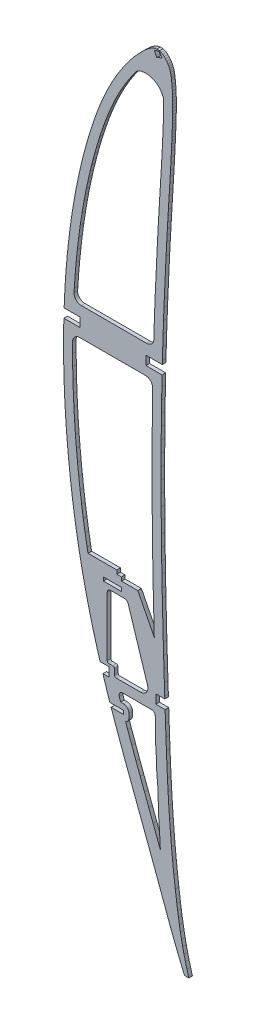
SolidWorks part; units mm, degrees
ref_plane "前视基准面" through (0, 0, 0) normal (0, 0, 1) x (1, 0, 0)
ref_plane "上视基准面" through (0, 0, 0) normal (0, 1, 0) x (1, 0, 0)
ref_plane "右视基准面" through (0, 0, 0) normal (1, 0, 0) x (0, 0, -1)
sketch "Model" plane through (0, 0, 0) normal (0, 0, 1) x (1, 0, 0)
  line L0 (54.2913, 117.0842) -> (54.2913, 119.0842)
  line L1 (43.2867, 175.5953) -> (43.2867, 177.5953)
  line L2 (47.5499, 117.0842) -> (54.2913, 117.0842)
  line L3 (54.2913, 119.0842) -> (46.8729, 119.0842)
  line L4 (41.4413, 135.9645) -> (46.4413, 135.9645)
  line L5 (46.4413, 135.9645) -> (46.4413, 130.9645)
  line L6 (72.3504, 135.9645) -> (72.3504, 130.9645)
  line L7 (72.3504, 135.9645) -> (77.3504, 135.9645)
  line L8 (77.5205, 130.9645) -> (72.3504, 130.9645)
  line L9 (42.9847, 130.9645) -> (46.4413, 130.9645)
  line L10 (45.5666, 122.9434) -> (43.4876, 129.3408)
  line L11 (43.4876, 129.3408) -> (42.9847, 130.9645)
  line L12 (41.4413, 135.9645) -> (40.6109, 138.7843)
  line L13 (77.1998, 140.4674) -> (77.3066, 137.2545)
  line L14 (77.3066, 137.2545) -> (77.3504, 135.9645)
  line L15 (77.5205, 130.9645) -> (77.5251, 130.8269)
  line L16 (77.5251, 130.8269) -> (77.7487, 124.3996)
  line L17 (77.7487, 124.3996) -> (77.9822, 117.9746)
  line L18 (77.9822, 117.9746) -> (78.009, 117.2896)
  line L19 (88.29, 8.5437) -> (88.0966, 8.9921)
  line L20 (88.0966, 8.9921) -> (86.7544, 12.1535)
  line L21 (86.7544, 12.1535) -> (85.4358, 15.3251)
  line L22 (85.4358, 15.3251) -> (84.1437, 18.5087)
  line L23 (84.1437, 18.5087) -> (82.9023, 21.6546)
  line L24 (82.9023, 21.6546) -> (81.6876, 24.8086)
  line L25 (81.6876, 24.8086) -> (80.4935, 27.9715)
  line L26 (80.4935, 27.9715) -> (79.3151, 31.1411)
  line L27 (79.3151, 31.1411) -> (78.1486, 34.3143)
  line L28 (78.1486, 34.3143) -> (76.9859, 37.4896)
  line L29 (76.9859, 37.4896) -> (75.8232, 40.6669)
  line L30 (75.8232, 40.6669) -> (73.4872, 47.013)
  line L31 (73.4872, 47.013) -> (71.1336, 53.3494)
  line L32 (71.1336, 53.3494) -> (68.7682, 59.6802)
  line L33 (68.7682, 59.6802) -> (66.394, 66.0067)
  line L34 (66.394, 66.0067) -> (64.0128, 72.3319)
  line L35 (64.0128, 72.3319) -> (61.6296, 78.6569)
  line L36 (61.6296, 78.6569) -> (59.2463, 84.986)
  line L37 (59.2463, 84.986) -> (56.8823, 91.2849)
  line L38 (56.8823, 91.2849) -> (54.5361, 97.5885)
  line L39 (54.5361, 97.5885) -> (52.2195, 103.9015)
  line L40 (52.2195, 103.9015) -> (49.9444, 110.2283)
  line L41 (49.9444, 110.2283) -> (47.9557, 115.9083)
  line L42 (78.009, 117.2896) -> (78.2336, 111.5505)
  line L43 (78.2336, 111.5505) -> (78.51, 105.1294)
  line L44 (78.51, 105.1294) -> (78.8173, 98.7097)
  line L45 (78.8173, 98.7097) -> (79.1646, 92.2908)
  line L46 (79.1646, 92.2908) -> (79.5579, 85.8728)
  line L47 (79.5579, 85.8728) -> (80.0046, 79.4492)
  line L48 (80.0046, 79.4492) -> (80.509, 73.0311)
  line L49 (80.509, 73.0311) -> (81.0722, 66.6185)
  line L50 (81.0722, 66.6185) -> (81.7013, 60.2119)
  line L51 (81.7013, 60.2119) -> (82.3972, 53.8101)
  line L52 (82.3972, 53.8101) -> (83.1659, 47.4146)
  line L53 (83.1659, 47.4146) -> (84.0104, 41.0243)
  line L54 (84.0104, 41.0243) -> (84.4661, 37.8092)
  line L55 (84.4661, 37.8092) -> (84.9486, 34.5991)
  line L56 (84.9486, 34.5991) -> (85.4639, 31.3946)
  line L57 (85.4639, 31.3946) -> (86.0178, 28.1987)
  line L58 (86.0178, 28.1987) -> (86.6183, 25.0129)
  line L59 (86.6183, 25.0129) -> (87.2714, 21.8383)
  line L60 (87.2714, 21.8383) -> (87.983, 18.6764)
  line L61 (87.983, 18.6764) -> (88.7727, 15.4677)
  line L62 (88.7727, 15.4677) -> (89.6209, 12.2737)
  line L63 (89.6209, 12.2737) -> (90.5165, 9.0917)
  line L64 (90.5165, 9.0917) -> (90.6781, 8.5437)
  line L65 (90.6781, 8.5437) -> (88.29, 8.5437)
  line L66 (72.0426, 125.2144) -> (72.2183, 117.7571)
  line L67 (72.2183, 117.7571) -> (72.3082, 111.0082)
  line L68 (72.3082, 111.0082) -> (72.7111, 105.0949)
  line L69 (72.7111, 105.0949) -> (72.8903, 98.4132)
  line L70 (72.8903, 98.4132) -> (73.4718, 91.9672)
  line L71 (73.4718, 91.9672) -> (73.6969, 85.8323)
  line L72 (73.6969, 85.8323) -> (73.7913, 79.2782)
  line L73 (73.7913, 79.2782) -> (74.3141, 72.7011)
  line L74 (74.3141, 72.7011) -> (74.6648, 66.3846)
  line L75 (74.6648, 66.3846) -> (74.8646, 62.2836)
  line L76 (74.8646, 62.2836) -> (73.2043, 66.7077)
  line L77 (73.2043, 66.7077) -> (70.8228, 73.0338)
  line L78 (70.8228, 73.0338) -> (68.4394, 79.3594)
  line L79 (68.4394, 79.3594) -> (66.0566, 85.6871)
  line L80 (66.0566, 85.6871) -> (63.694, 91.9824)
  line L81 (63.694, 91.9824) -> (61.3503, 98.2791)
  line L82 (61.3503, 98.2791) -> (59.0376, 104.5817)
  line L83 (59.0376, 104.5817) -> (56.7675, 110.8944)
  line L84 (56.7675, 110.8944) -> (55.6091, 114.203)
  line L85 (57.4411, 116.9663) -> (57.4411, 119.1909)
  line L86 (54.4411, 122.1909) -> (52.8701, 122.1909)
  line L87 (52.8701, 122.1909) -> (52.0797, 124.526)
  line L88 (53.9741, 127.1673) -> (70.0431, 127.1673)
  line L89 (45.3607, 138.4853) -> (45.3607, 171.1109)
  line L90 (47.3607, 173.1109) -> (55.0651, 173.1109)
  line L91 (56.9714, 171.716) -> (67.7492, 137.7647)
  line L92 (50.459, 132.5544) -> (63.9367, 132.5544)
  line L93 (47.5499, 117.0842) -> (47.9557, 115.9083)
  line L94 (43.2867, 175.5953) -> (53.2867, 175.5953)
  line L95 (46.8729, 119.0842) -> (45.5666, 122.9434)
  line L96 (53.2867, 175.5953) -> (53.2867, 177.5953)
  line L97 (50.7445, 177.5953) -> (53.2867, 177.5953)
  line L98 (50.7445, 182.5953) -> (53.2867, 182.5953)
  line L99 (21.4859, 295.9645) -> (21.7513, 302.1442)
  line L100 (21.7513, 302.1442) -> (22.12, 308.5794)
  line L101 (22.12, 308.5794) -> (22.5856, 315.0859)
  line L102 (22.5856, 315.0859) -> (23.1507, 321.5827)
  line L103 (23.1507, 321.5827) -> (23.8184, 328.069)
  line L104 (23.8184, 328.069) -> (24.5928, 334.5419)
  line L105 (24.5928, 334.5419) -> (25.481, 340.9998)
  line L106 (25.481, 340.9998) -> (26.486, 347.4408)
  line L107 (26.486, 347.4408) -> (27.612, 353.862)
  line L108 (27.612, 353.862) -> (28.2359, 357.1334)
  line L109 (28.2359, 357.1334) -> (28.8931, 360.3981)
  line L110 (28.8931, 360.3981) -> (29.5827, 363.6553)
  line L111 (29.5827, 363.6553) -> (30.3077, 366.904)
  line L112 (30.3077, 366.904) -> (31.066, 370.1462)
  line L113 (31.066, 370.1462) -> (31.8597, 373.3799)
  line L114 (31.8597, 373.3799) -> (32.6898, 376.6052)
  line L115 (32.6898, 376.6052) -> (33.5785, 379.9081)
  line L116 (33.5785, 379.9081) -> (34.5079, 383.1987)
  line L117 (34.5079, 383.1987) -> (35.4798, 386.4773)
  line L118 (35.4798, 386.4773) -> (36.4974, 389.7408)
  line L119 (36.4974, 389.7408) -> (37.5627, 392.9903)
  line L120 (37.5627, 392.9903) -> (38.6787, 396.2231)
  line L121 (38.6787, 396.2231) -> (39.8486, 399.4392)
  line L122 (39.8486, 399.4392) -> (40.4777, 401.1002)
  line L123 (40.4777, 401.1002) -> (41.1222, 402.7549)
  line L124 (72.0622, 328.3115) -> (71.885, 324.0494)
  line L125 (71.885, 324.0494) -> (71.6364, 317.5859)
  line L126 (71.6364, 317.5859) -> (71.408, 311.1173)
  line L127 (71.408, 311.1173) -> (71.2921, 305.8066)
  line L128 (67.2931, 301.8939) -> (30.9809, 301.8939)
  line L129 (26.9874, 306.1227) -> (27.1097, 308.2579)
  line L130 (27.1097, 308.2579) -> (27.5701, 314.6907)
  line L131 (27.5701, 314.6907) -> (28.1285, 321.11)
  line L132 (28.1285, 321.11) -> (28.7879, 327.516)
  line L133 (28.7879, 327.516) -> (29.5522, 333.9043)
  line L134 (29.5522, 333.9043) -> (30.4282, 340.2737)
  line L135 (30.4282, 340.2737) -> (31.419, 346.6235)
  line L136 (31.419, 346.6235) -> (32.5304, 352.9618)
  line L137 (32.5304, 352.9618) -> (33.1426, 356.1716)
  line L138 (33.1426, 356.1716) -> (33.7898, 359.3869)
  line L139 (33.7898, 359.3869) -> (34.4686, 362.593)
  line L140 (34.4686, 362.593) -> (35.1821, 365.7901)
  line L141 (35.1821, 365.7901) -> (35.9283, 368.9809)
  line L142 (35.9283, 368.9809) -> (36.7088, 372.1608)
  line L143 (36.7088, 372.1608) -> (37.5251, 375.3324)
  line L144 (37.5251, 375.3324) -> (38.3987, 378.5789)
  line L145 (38.3987, 378.5789) -> (39.3109, 381.8087)
  line L146 (39.3109, 381.8087) -> (40.2636, 385.0224)
  line L147 (40.2636, 385.0224) -> (41.2599, 388.2177)
  line L148 (41.2599, 388.2177) -> (42.3017, 391.3956)
  line L149 (42.3017, 391.3956) -> (43.3916, 394.5525)
  line L150 (43.3916, 394.5525) -> (44.5361, 397.699)
  line L151 (44.5361, 397.699) -> (45.1453, 399.3073)
  line L152 (45.1453, 399.3073) -> (45.7724, 400.9174)
  line L153 (40.6109, 138.7843) -> (39.6813, 141.9408)
  line L154 (39.6813, 141.9408) -> (37.9112, 148.2786)
  line L155 (37.9112, 148.2786) -> (36.2331, 154.6415)
  line L156 (36.2331, 154.6415) -> (34.647, 161.0284)
  line L157 (34.647, 161.0284) -> (33.1549, 167.4384)
  line L158 (33.1549, 167.4384) -> (31.758, 173.8716)
  line L159 (31.758, 173.8716) -> (30.4769, 180.2187)
  line L160 (30.4769, 180.2187) -> (29.2883, 186.5809)
  line L161 (29.2883, 186.5809) -> (28.189, 192.9591)
  line L162 (28.189, 192.9591) -> (27.1742, 199.3509)
  line L163 (27.1742, 199.3509) -> (26.244, 205.7564)
  line L164 (26.244, 205.7564) -> (25.3942, 212.1734)
  line L165 (25.3942, 212.1734) -> (24.6221, 218.6029)
  line L166 (24.6221, 218.6029) -> (23.9293, 225.0007)
  line L167 (23.9293, 225.0007) -> (23.3124, 231.4049)
  line L168 (23.3124, 231.4049) -> (22.7713, 237.8144)
  line L169 (22.7713, 237.8144) -> (22.3071, 244.2283)
  line L170 (22.3071, 244.2283) -> (21.9207, 250.6485)
  line L171 (21.9207, 250.6485) -> (21.6121, 257.0742)
  line L172 (21.6121, 257.0742) -> (21.3834, 263.5043)
  line L173 (21.3834, 263.5043) -> (21.2343, 269.946)
  line L174 (21.2343, 269.946) -> (21.1672, 276.3872)
  line L175 (21.1672, 276.3872) -> (21.1843, 282.828)
  line L176 (21.1843, 282.828) -> (21.2855, 289.2686)
  line L177 (21.2855, 289.2686) -> (21.3104, 290.9645)
  line L178 (34.7295, 184.6822) -> (34.2097, 187.4647)
  line L179 (34.2097, 187.4647) -> (33.122, 193.7757)
  line L180 (33.122, 193.7757) -> (32.1176, 200.1022)
  line L181 (32.1176, 200.1022) -> (31.1966, 206.4439)
  line L182 (31.1966, 206.4439) -> (30.3549, 212.7997)
  line L183 (30.3549, 212.7997) -> (29.5899, 219.1701)
  line L184 (29.5899, 219.1701) -> (28.9034, 225.5096)
  line L185 (28.9034, 225.5096) -> (28.2922, 231.855)
  line L186 (28.2922, 231.855) -> (27.7561, 238.2052)
  line L187 (27.7561, 238.2052) -> (27.2962, 244.559)
  line L188 (27.2962, 244.559) -> (26.9135, 250.9187)
  line L189 (26.9135, 250.9187) -> (26.6078, 257.283)
  line L190 (26.6078, 257.283) -> (26.3813, 263.6511)
  line L191 (26.3813, 263.6511) -> (26.2337, 270.0298)
  line L192 (26.2337, 270.0298) -> (26.1673, 276.4066)
  line L193 (26.1673, 276.4066) -> (26.1741, 282.1401)
  line L194 (30.1736, 286.0773) -> (66.61, 286.0773)
  line L195 (70.6099, 282.0473) -> (70.5858, 278.8357)
  line L196 (70.5858, 278.8357) -> (70.4844, 272.3768)
  line L197 (70.4844, 272.3768) -> (70.4042, 265.917)
  line L198 (70.4042, 265.917) -> (70.3448, 259.4645)
  line L199 (70.3448, 259.4645) -> (70.3053, 253.0146)
  line L200 (70.3053, 253.0146) -> (70.2849, 246.5668)
  line L201 (70.2849, 246.5668) -> (70.2835, 240.1186)
  line L202 (70.2835, 240.1186) -> (70.2992, 233.6716)
  line L203 (70.2992, 233.6716) -> (70.333, 227.2236)
  line L204 (70.333, 227.2236) -> (70.3829, 220.7743)
  line L205 (70.3829, 220.7743) -> (70.4486, 214.33)
  line L206 (70.4486, 214.33) -> (70.5294, 207.8878)
  line L207 (70.5294, 207.8878) -> (70.6251, 201.4472)
  line L208 (70.6251, 201.4472) -> (70.7358, 195.0062)
  line L209 (70.7358, 195.0062) -> (70.8615, 188.5677)
  line L210 (70.8615, 188.5677) -> (70.9645, 183.7938)
  line L211 (41.1222, 402.7549) -> (41.7829, 404.4033)
  line L212 (41.7829, 404.4033) -> (42.461, 406.0424)
  line L213 (42.461, 406.0424) -> (43.1575, 407.6743)
  line L214 (43.1575, 407.6743) -> (43.5048, 408.4903)
  line L215 (43.5048, 408.4903) -> (44.2402, 410.1019)
  line L216 (44.2402, 410.1019) -> (45.4014, 412.5869)
  line L217 (45.4014, 412.5869) -> (46.2184, 414.2541)
  line L218 (46.2184, 414.2541) -> (47.059, 415.9103)
  line L219 (47.059, 415.9103) -> (47.9251, 417.5547)
  line L220 (47.9251, 417.5547) -> (48.8176, 419.1902)
  line L221 (48.8176, 419.1902) -> (49.7376, 420.8159)
  line L222 (49.7376, 420.8159) -> (50.6849, 422.4337)
  line L223 (50.6849, 422.4337) -> (51.7401, 424.1714)
  line L224 (51.7401, 424.1714) -> (52.8271, 425.8924)
  line L225 (52.8271, 425.8924) -> (53.943, 427.5917)
  line L226 (53.943, 427.5917) -> (55.0852, 429.2632)
  line L227 (55.0852, 429.2632) -> (56.2519, 430.8986)
  line L228 (56.2519, 430.8986) -> (57.4405, 432.494)
  line L229 (57.4405, 432.494) -> (58.6501, 434.0422)
  line L230 (58.6501, 434.0422) -> (59.4024, 434.9689)
  line L231 (59.4024, 434.9689) -> (60.1683, 435.8822)
  line L232 (60.1683, 435.8822) -> (60.9535, 436.7883)
  line L233 (60.9535, 436.7883) -> (61.7657, 437.6956)
  line L234 (61.7657, 437.6956) -> (62.6097, 438.6093)
  line L235 (62.6097, 438.6093) -> (63.493, 439.5377)
  line L236 (63.493, 439.5377) -> (64.4215, 440.4871)
  line L237 (64.4215, 440.4871) -> (65.7171, 441.7628)
  line L238 (65.7171, 441.7628) -> (67.0851, 443.0077)
  line L239 (67.0851, 443.0077) -> (68.507, 444.1418)
  line L240 (68.507, 444.1418) -> (69.9631, 445.0862)
  line L241 (69.9631, 445.0862) -> (71.4391, 445.7622)
  line L242 (71.4391, 445.7622) -> (72.9132, 446.0898)
  line L243 (72.9132, 446.0898) -> (74.3699, 445.9893)
  line L244 (74.3699, 445.9893) -> (74.9691, 445.7828)
  line L245 (45.7724, 400.9174) -> (46.4137, 402.5173)
  line L246 (46.4137, 402.5173) -> (47.0706, 404.1053)
  line L247 (47.0706, 404.1053) -> (47.7446, 405.6845)
  line L248 (47.7446, 405.6845) -> (48.4346, 407.2497)
  line L249 (48.4346, 407.2497) -> (49.1428, 408.8016)
  line L250 (49.1428, 408.8016) -> (49.9068, 410.4185)
  line L251 (49.9068, 410.4185) -> (50.6929, 412.0224)
  line L252 (50.6929, 412.0224) -> (51.5005, 413.6138)
  line L253 (51.5005, 413.6138) -> (52.3317, 415.1919)
  line L254 (52.3317, 415.1919) -> (53.1881, 416.7612)
  line L255 (53.1881, 416.7612) -> (54.0709, 418.3212)
  line L256 (54.0709, 418.3212) -> (54.9794, 419.8727)
  line L257 (54.9794, 419.8727) -> (55.991, 421.5386)
  line L258 (55.991, 421.5386) -> (57.0308, 423.185)
  line L259 (57.0308, 423.185) -> (58.0971, 424.8087)
  line L260 (58.0971, 424.8087) -> (59.1848, 426.4004)
  line L261 (59.1848, 426.4004) -> (60.2923, 427.9528)
  line L262 (60.2923, 427.9528) -> (61.4158, 429.4608)
  line L263 (61.4158, 429.4608) -> (61.5587, 429.6437)
  line L264 (74.9691, 445.7828) -> (75.2622, 445.6819)
  line L265 (75.2622, 445.6819) -> (76.127, 445.2022)
  line L266 (76.127, 445.2022) -> (76.952, 444.5775)
  line L267 (76.952, 444.5775) -> (77.7222, 443.8334)
  line L268 (77.7222, 443.8334) -> (78.4264, 442.9964)
  line L269 (78.4264, 442.9964) -> (79.0504, 442.0927)
  line L270 (79.0504, 442.0927) -> (79.581, 441.149)
  line L271 (79.581, 441.149) -> (79.9676, 440.297)
  line L272 (79.9676, 440.297) -> (80.2815, 439.4339)
  line L273 (80.2815, 439.4339) -> (80.5317, 438.564)
  line L274 (80.5317, 438.564) -> (80.7311, 437.6868)
  line L275 (80.7311, 437.6868) -> (80.8889, 436.8029)
  line L276 (80.8889, 436.8029) -> (81.0167, 435.9146)
  line L277 (81.0167, 435.9146) -> (81.1237, 435.0234)
  line L278 (81.1237, 435.0234) -> (81.2894, 433.4301)
  line L279 (81.2894, 433.4301) -> (81.4273, 431.8306)
  line L280 (81.4273, 431.8306) -> (81.5383, 430.2269)
  line L281 (81.5383, 430.2269) -> (81.6245, 428.6202)
  line L282 (81.6245, 428.6202) -> (81.6877, 427.0114)
  line L283 (81.6877, 427.0114) -> (81.729, 425.4007)
  line L284 (81.729, 425.4007) -> (81.7503, 423.7901)
  line L285 (81.7503, 423.7901) -> (81.7526, 422.1776)
  line L286 (81.7526, 422.1776) -> (81.7389, 420.5655)
  line L287 (81.7389, 420.5655) -> (81.7111, 418.9558)
  line L288 (81.7111, 418.9558) -> (81.6723, 417.3465)
  line L289 (81.6723, 417.3465) -> (81.6234, 415.7369)
  line L290 (81.6234, 415.7369) -> (81.5686, 414.1279)
  line L291 (81.5686, 414.1279) -> (81.5087, 412.5188)
  line L292 (81.5087, 412.5188) -> (81.447, 410.9066)
  line L293 (81.447, 410.9066) -> (81.3832, 409.2953)
  line L294 (81.3832, 409.2953) -> (81.3164, 407.6838)
  line L295 (81.3164, 407.6838) -> (81.2476, 406.0723)
  line L296 (81.2476, 406.0723) -> (81.1759, 404.4606)
  line L297 (81.1759, 404.4606) -> (81.1021, 402.8489)
  line L298 (81.1021, 402.8489) -> (81.0243, 401.2369)
  line L299 (81.0243, 401.2369) -> (80.861, 398.0097)
  line L300 (80.861, 398.0097) -> (80.6865, 394.7831)
  line L301 (80.6865, 394.7831) -> (80.503, 391.558)
  line L302 (80.503, 391.558) -> (80.3125, 388.3336)
  line L303 (80.3125, 388.3336) -> (80.118, 385.109)
  line L304 (80.118, 385.109) -> (79.9214, 381.8844)
  line L305 (79.9214, 381.8844) -> (79.724, 378.6587)
  line L306 (79.724, 378.6587) -> (79.5285, 375.4331)
  line L307 (79.5285, 375.4331) -> (79.334, 372.2076)
  line L308 (79.334, 372.2076) -> (79.1424, 368.9831)
  line L309 (79.1424, 368.9831) -> (78.954, 365.7579)
  line L310 (78.954, 365.7579) -> (78.7695, 362.5327)
  line L311 (78.7695, 362.5327) -> (78.587, 359.3067)
  line L312 (78.587, 359.3067) -> (78.4096, 356.0799)
  line L313 (78.4096, 356.0799) -> (78.0431, 349.1751)
  line L314 (76.7504, 423.6864) -> (76.7526, 422.1952)
  line L315 (76.7526, 422.1952) -> (76.7393, 420.6299)
  line L316 (76.7393, 420.6299) -> (76.7122, 419.0593)
  line L317 (76.7122, 419.0593) -> (76.6741, 417.4827)
  line L318 (76.6741, 417.4827) -> (76.626, 415.8979)
  line L319 (76.626, 415.8979) -> (76.5717, 414.3061)
  line L320 (76.5717, 414.3061) -> (76.5123, 412.7074)
  line L321 (76.5123, 412.7074) -> (76.4508, 411.1011)
  line L322 (76.4508, 411.1011) -> (76.3873, 409.4976)
  line L323 (76.3873, 409.4976) -> (76.3208, 407.8939)
  line L324 (76.3208, 407.8939) -> (76.2524, 406.2901)
  line L325 (76.2524, 406.2901) -> (76.181, 404.6861)
  line L326 (76.181, 404.6861) -> (76.1076, 403.0836)
  line L327 (76.1076, 403.0836) -> (76.0304, 401.4838)
  line L328 (76.0304, 401.4838) -> (75.8678, 398.2711)
  line L329 (75.8678, 398.2711) -> (75.6942, 395.06)
  line L330 (75.6942, 395.06) -> (75.5114, 391.8475)
  line L331 (75.5114, 391.8475) -> (75.3214, 388.6316)
  line L332 (75.3214, 388.6316) -> (75.127, 385.4101)
  line L333 (75.127, 385.4101) -> (74.9307, 382.1886)
  line L334 (74.9307, 382.1886) -> (74.7333, 378.9643)
  line L335 (74.7333, 378.9643) -> (74.5376, 375.7356)
  line L336 (74.5376, 375.7356) -> (74.343, 372.5085)
  line L337 (74.343, 372.5085) -> (74.1512, 369.2796)
  line L338 (74.1512, 369.2796) -> (73.9623, 366.0465)
  line L339 (73.9623, 366.0465) -> (73.7776, 362.8183)
  line L340 (73.7776, 362.8183) -> (73.5948, 359.5851)
  line L341 (73.5948, 359.5851) -> (73.4169, 356.3497)
  line L342 (73.4169, 356.3497) -> (73.0485, 349.4086)
  line L343 (77.0568, 328.078) -> (76.881, 323.8495)
  line L344 (76.881, 323.8495) -> (76.633, 317.4016)
  line L345 (76.633, 317.4016) -> (76.4052, 310.9495)
  line L346 (76.4052, 310.9495) -> (76.2, 304.5084)
  line L347 (76.2, 304.5084) -> (76.0147, 298.0682)
  line L348 (76.0147, 298.0682) -> (75.9611, 295.9645)
  line L349 (75.8357, 290.9645) -> (75.7072, 285.1895)
  line L350 (75.7072, 285.1895) -> (75.585, 278.7491)
  line L351 (75.585, 278.7491) -> (75.4839, 272.3065)
  line L352 (75.4839, 272.3065) -> (75.4039, 265.8629)
  line L353 (75.4039, 265.8629) -> (75.3446, 259.4262)
  line L354 (75.3446, 259.4262) -> (75.3053, 252.9914)
  line L355 (75.3053, 252.9914) -> (75.2849, 246.5584)
  line L356 (75.2849, 246.5584) -> (75.2835, 240.1242)
  line L357 (75.2835, 240.1242) -> (75.2992, 233.6907)
  line L358 (75.2992, 233.6907) -> (75.3329, 227.2561)
  line L359 (75.3329, 227.2561) -> (75.3827, 220.8191)
  line L360 (75.3827, 220.8191) -> (75.4483, 214.3869)
  line L361 (75.4483, 214.3869) -> (75.5289, 207.9563)
  line L362 (75.5289, 207.9563) -> (75.6244, 201.5273)
  line L363 (75.6244, 201.5273) -> (75.735, 195.098)
  line L364 (75.735, 195.098) -> (75.8605, 188.6704)
  line L365 (75.8605, 188.6704) -> (75.9628, 183.9217)
  line L366 (76.5026, 162.8246) -> (76.6882, 156.5299)
  line L367 (76.6882, 156.5299) -> (76.8866, 150.1054)
  line L368 (76.8866, 150.1054) -> (77.0931, 143.6803)
  line L369 (77.0931, 143.6803) -> (77.1998, 140.4674)
  line L370 (75.9628, 183.9217) -> (76.5026, 162.8246)
  line L371 (70.9645, 183.7938) -> (71.5042, 162.6645)
  line L372 (78.0431, 349.1751) -> (77.0568, 328.078)
  line L373 (73.0485, 349.4086) -> (72.0622, 328.3115)
  line L374 (74.3647, 445.9736) -> (71.6586, 444.6787)
  line L375 (71.6586, 444.6787) -> (72.9535, 441.9726)
  line L376 (72.9535, 441.9726) -> (75.6596, 443.2675)
  line L377 (75.6596, 443.2675) -> (74.3647, 445.9736)
  line L378 (21.4859, 295.9645) -> (29.4089, 295.9645)
  line L379 (67.8973, 295.9645) -> (75.9611, 295.9645)
  line L380 (34.7295, 184.6822) -> (50.7445, 184.6822)
  line L381 (53.2867, 180.5953) -> (62.3706, 180.5953)
  line L382 (62.3706, 180.5953) -> (71.5042, 162.6645)
  line L383 (50.7445, 184.6822) -> (50.7445, 182.5953)
  line L384 (53.2867, 182.5953) -> (53.2867, 180.5953)
  line L385 (46.3607, 137.4853) -> (48.459, 137.4853)
  line L386 (49.459, 136.4853) -> (49.459, 133.5544)
  line L387 (66.8973, 290.9645) -> (66.8973, 295.9645)
  line L388 (66.8973, 295.9645) -> (67.8973, 295.9645)
  line L389 (30.4087, 290.9645) -> (30.4087, 295.9645)
  line L390 (30.4087, 295.9645) -> (29.4089, 295.9645)
  line L391 (30.4087, 290.9645) -> (21.3104, 290.9645)
  line L392 (66.8973, 290.9645) -> (75.8357, 290.9645)
  line L393 (43.2867, 177.5953) -> (50.7445, 177.5953)
  line L394 (63.0149, 430.7237) -> (63.0049, 430.7177)
  line L395 (63.0049, 430.7177) -> (62.9949, 430.7127)
  line L396 (62.9949, 430.7127) -> (62.9849, 430.7067)
  line L397 (62.9849, 430.7067) -> (62.9749, 430.7007)
  line L398 (62.9749, 430.7007) -> (62.9649, 430.6947)
  line L399 (62.9649, 430.6947) -> (62.9549, 430.6887)
  line L400 (62.9549, 430.6887) -> (62.9449, 430.6827)
  line L401 (62.9449, 430.6827) -> (62.9349, 430.6767)
  line L402 (62.9349, 430.6767) -> (62.9249, 430.6707)
  line L403 (62.9249, 430.6707) -> (62.9149, 430.6657)
  line L404 (62.9149, 430.6657) -> (62.9049, 430.6597)
  line L405 (62.9049, 430.6597) -> (62.8949, 430.6537)
  line L406 (62.8949, 430.6537) -> (62.8849, 430.6477)
  line L407 (62.8849, 430.6477) -> (62.8749, 430.6417)
  line L408 (62.8749, 430.6417) -> (62.8649, 430.6357)
  line L409 (62.8649, 430.6357) -> (62.8549, 430.6297)
  line L410 (62.8549, 430.6297) -> (62.8449, 430.6237)
  line L411 (62.8449, 430.6237) -> (62.8349, 430.6177)
  line L412 (62.8349, 430.6177) -> (62.8249, 430.6117)
  line L413 (62.8249, 430.6117) -> (62.8149, 430.6057)
  line L414 (62.8149, 430.6057) -> (62.8049, 430.5997)
  line L415 (62.8049, 430.5997) -> (62.7949, 430.5937)
  line L416 (62.7949, 430.5937) -> (62.7849, 430.5877)
  line L417 (62.7849, 430.5877) -> (62.7749, 430.5827)
  line L418 (62.7749, 430.5827) -> (62.7649, 430.5767)
  line L419 (62.7649, 430.5767) -> (62.7549, 430.5707)
  line L420 (62.7549, 430.5707) -> (62.7449, 430.5647)
  line L421 (62.7449, 430.5647) -> (62.7349, 430.5587)
  line L422 (62.7349, 430.5587) -> (62.7249, 430.5517)
  line L423 (62.7249, 430.5517) -> (62.7149, 430.5457)
  line L424 (62.7149, 430.5457) -> (62.7049, 430.5397)
  line L425 (62.7049, 430.5397) -> (62.6949, 430.5337)
  line L426 (62.6949, 430.5337) -> (62.6849, 430.5277)
  line L427 (62.6849, 430.5277) -> (62.6849, 430.5217)
  line L428 (62.6849, 430.5217) -> (62.6749, 430.5157)
  line L429 (62.6749, 430.5157) -> (62.6649, 430.5097)
  line L430 (62.6649, 430.5097) -> (62.6549, 430.5037)
  line L431 (62.6549, 430.5037) -> (62.6449, 430.4977)
  line L432 (62.6449, 430.4977) -> (62.6349, 430.4917)
  line L433 (62.6349, 430.4917) -> (62.6249, 430.4857)
  line L434 (62.6249, 430.4857) -> (62.6149, 430.4797)
  line L435 (62.6149, 430.4797) -> (62.6049, 430.4727)
  line L436 (62.6049, 430.4727) -> (62.5949, 430.4667)
  line L437 (62.5949, 430.4667) -> (62.5849, 430.4607)
  line L438 (62.5849, 430.4607) -> (62.5749, 430.4547)
  line L439 (62.5749, 430.4547) -> (62.5649, 430.4487)
  line L440 (62.5649, 430.4487) -> (62.5549, 430.4417)
  line L441 (62.5549, 430.4417) -> (62.5449, 430.4357)
  line L442 (62.5449, 430.4357) -> (62.5349, 430.4297)
  line L443 (62.5349, 430.4297) -> (62.5249, 430.4237)
  line L444 (62.5249, 430.4237) -> (62.5149, 430.4167)
  line L445 (62.5149, 430.4167) -> (62.5049, 430.4107)
  line L446 (62.5049, 430.4107) -> (62.4949, 430.4047)
  line L447 (62.4949, 430.4047) -> (62.4849, 430.3987)
  line L448 (62.4849, 430.3987) -> (62.4749, 430.3917)
  line L449 (62.4749, 430.3917) -> (62.4649, 430.3857)
  line L450 (62.4649, 430.3857) -> (62.4549, 430.3797)
  line L451 (62.4549, 430.3797) -> (62.4549, 430.3727)
  line L452 (62.4549, 430.3727) -> (62.4449, 430.3667)
  line L453 (62.4449, 430.3667) -> (62.4349, 430.3607)
  line L454 (62.4349, 430.3607) -> (62.4249, 430.3537)
  line L455 (62.4249, 430.3537) -> (62.4149, 430.3477)
  line L456 (62.4149, 430.3477) -> (62.4049, 430.3407)
  line L457 (62.4049, 430.3407) -> (62.3949, 430.3347)
  line L458 (62.3949, 430.3347) -> (62.3849, 430.3277)
  line L459 (62.3849, 430.3277) -> (62.3749, 430.3217)
  line L460 (62.3749, 430.3217) -> (62.3649, 430.3157)
  line L461 (62.3649, 430.3157) -> (62.3549, 430.3087)
  line L462 (62.3549, 430.3087) -> (62.3449, 430.3027)
  line L463 (62.3449, 430.3027) -> (62.3349, 430.2957)
  line L464 (62.3349, 430.2957) -> (62.3249, 430.2887)
  line L465 (62.3249, 430.2887) -> (62.3149, 430.2827)
  line L466 (62.3149, 430.2827) -> (62.3049, 430.2757)
  line L467 (62.3049, 430.2757) -> (62.3049, 430.2697)
  line L468 (62.3049, 430.2697) -> (62.2949, 430.2627)
  line L469 (62.2949, 430.2627) -> (62.2849, 430.2557)
  line L470 (62.2849, 430.2557) -> (62.2749, 430.2497)
  line L471 (62.2749, 430.2497) -> (62.2649, 430.2427)
  line L472 (62.2649, 430.2427) -> (62.2549, 430.2357)
  line L473 (62.2549, 430.2357) -> (62.2449, 430.2297)
  line L474 (62.2449, 430.2297) -> (62.2349, 430.2227)
  line L475 (62.2349, 430.2227) -> (62.2249, 430.2157)
  line L476 (62.2249, 430.2157) -> (62.2149, 430.2097)
  line L477 (62.2149, 430.2097) -> (62.2049, 430.2027)
  line L478 (62.2049, 430.2027) -> (62.1949, 430.1957)
  line L479 (62.1949, 430.1957) -> (62.1849, 430.1887)
  line L480 (62.1849, 430.1887) -> (62.1849, 430.1817)
  line L481 (62.1849, 430.1817) -> (62.1749, 430.1757)
  line L482 (62.1749, 430.1757) -> (62.1649, 430.1687)
  line L483 (62.1649, 430.1687) -> (62.1549, 430.1617)
  line L484 (62.1549, 430.1617) -> (62.1449, 430.1547)
  line L485 (62.1449, 430.1547) -> (62.1349, 430.1477)
  line L486 (62.1349, 430.1477) -> (62.1249, 430.1407)
  line L487 (62.1249, 430.1407) -> (62.1149, 430.1337)
  line L488 (62.1149, 430.1337) -> (62.1049, 430.1267)
  line L489 (62.1049, 430.1267) -> (62.0949, 430.1197)
  line L490 (62.0949, 430.1197) -> (62.0849, 430.1127)
  line L491 (62.0849, 430.1127) -> (62.0849, 430.1057)
  line L492 (62.0849, 430.1057) -> (62.0749, 430.0987)
  line L493 (62.0749, 430.0987) -> (62.0649, 430.0917)
  line L494 (62.0649, 430.0917) -> (62.0549, 430.0847)
  line L495 (62.0549, 430.0847) -> (62.0449, 430.0777)
  line L496 (62.0449, 430.0777) -> (62.0349, 430.0707)
  line L497 (62.0349, 430.0707) -> (62.0249, 430.0637)
  line L498 (62.0249, 430.0637) -> (62.0149, 430.0567)
  line L499 (62.0149, 430.0567) -> (62.0049, 430.0487)
  line L500 (62.0049, 430.0487) -> (61.9949, 430.0417)
  line L501 (61.9949, 430.0417) -> (61.9949, 430.0347)
  line L502 (61.9949, 430.0347) -> (61.9849, 430.0277)
  line L503 (61.9849, 430.0277) -> (61.9749, 430.0207)
  line L504 (61.9749, 430.0207) -> (61.9649, 430.0127)
  line L505 (61.9649, 430.0127) -> (61.9549, 430.0057)
  line L506 (61.9549, 430.0057) -> (61.9449, 429.9987)
  line L507 (61.9449, 429.9987) -> (61.9349, 429.9907)
  line L508 (61.9349, 429.9907) -> (61.9249, 429.9837)
  line L509 (61.9249, 429.9837) -> (61.9149, 429.9767)
  line L510 (61.9149, 429.9767) -> (61.9149, 429.9687)
  line L511 (61.9149, 429.9687) -> (61.9049, 429.9617)
  line L512 (61.9049, 429.9617) -> (61.8949, 429.9547)
  line L513 (61.8949, 429.9547) -> (61.8849, 429.9467)
  line L514 (61.8849, 429.9467) -> (61.8749, 429.9397)
  line L515 (61.8749, 429.9397) -> (61.8649, 429.9317)
  line L516 (61.8649, 429.9317) -> (61.8549, 429.9247)
  line L517 (61.8549, 429.9247) -> (61.8549, 429.9167)
  line L518 (61.8549, 429.9167) -> (61.8449, 429.9097)
  line L519 (61.8449, 429.9097) -> (61.8349, 429.9017)
  line L520 (61.8349, 429.9017) -> (61.8249, 429.8947)
  line L521 (61.8249, 429.8947) -> (61.8149, 429.8867)
  line L522 (61.8149, 429.8867) -> (61.8049, 429.8797)
  line L523 (61.8049, 429.8797) -> (61.7949, 429.8717)
  line L524 (61.7949, 429.8717) -> (61.7949, 429.8647)
  line L525 (61.7949, 429.8647) -> (61.7849, 429.8567)
  line L526 (61.7849, 429.8567) -> (61.7749, 429.8487)
  line L527 (61.7749, 429.8487) -> (61.7649, 429.8417)
  line L528 (61.7649, 429.8417) -> (61.7549, 429.8337)
  line L529 (61.7549, 429.8337) -> (61.7449, 429.8257)
  line L530 (61.7449, 429.8257) -> (61.7349, 429.8177)
  line L531 (61.7349, 429.8177) -> (61.7349, 429.8107)
  line L532 (61.7349, 429.8107) -> (61.7249, 429.8027)
  line L533 (61.7249, 429.8027) -> (61.7149, 429.7947)
  line L534 (61.7149, 429.7947) -> (61.7049, 429.7867)
  line L535 (61.7049, 429.7867) -> (61.6949, 429.7797)
  line L536 (61.6949, 429.7797) -> (61.6849, 429.7717)
  line L537 (61.6849, 429.7717) -> (61.6849, 429.7637)
  line L538 (61.6849, 429.7637) -> (61.6749, 429.7557)
  line L539 (61.6749, 429.7557) -> (61.6649, 429.7477)
  line L540 (61.6649, 429.7477) -> (61.6549, 429.7397)
  line L541 (61.6549, 429.7397) -> (61.6449, 429.7317)
  line L542 (61.6449, 429.7317) -> (61.6349, 429.7237)
  line L543 (61.6349, 429.7237) -> (61.6349, 429.7157)
  line L544 (61.6349, 429.7157) -> (61.6249, 429.7077)
  line L545 (61.6249, 429.7077) -> (61.6149, 429.6997)
  line L546 (61.6149, 429.6997) -> (61.6049, 429.6917)
  line L547 (61.6049, 429.6917) -> (61.5949, 429.6837)
  line L548 (61.5949, 429.6837) -> (61.5949, 429.6757)
  line L549 (61.5949, 429.6757) -> (61.5849, 429.6677)
  line L550 (61.5849, 429.6677) -> (61.5749, 429.6597)
  line L551 (61.5749, 429.6597) -> (61.5649, 429.6517)
  line L552 (61.5649, 429.6517) -> (61.5587, 429.6437)
  arc A0 (47.3607, 173.1109) -> (45.3607, 171.1109) centre (47.3607, 171.1109) ccw
  arc A1 (56.9714, 171.716) -> (55.0651, 173.1109) centre (55.0651, 171.1109) ccw
  arc A2 (49.459, 133.5544) -> (50.459, 132.5544) centre (50.459, 133.5544) ccw
  arc A3 (63.9367, 132.5544) -> (67.7492, 137.7647) centre (63.9367, 136.5544) ccw
  arc A4 (76.7504, 423.6864) -> (63.0149, 430.7237) centre (66.7705, 421.1306) ccw
  arc A5 (45.3607, 138.4853) -> (46.3607, 137.4853) centre (46.3607, 138.4853) ccw
  arc A6 (49.459, 136.4853) -> (48.459, 137.4853) centre (48.459, 136.4853) ccw
  arc A7 (55.6091, 114.203) -> (57.4411, 116.9663) centre (54.4411, 116.9663) ccw
  arc A8 (57.4411, 119.1909) -> (54.4411, 122.1909) centre (54.4411, 119.1909) ccw
  arc A9 (53.9741, 127.1673) -> (52.0797, 124.526) centre (53.9741, 125.1673) ccw
  arc A10 (72.0426, 125.2144) -> (70.0431, 127.1673) centre (70.0431, 125.1673) ccw
  arc A11 (67.2931, 301.8939) -> (71.2921, 305.8066) centre (67.2931, 305.8939) ccw
  arc A12 (26.9874, 306.1227) -> (30.9809, 301.8939) centre (30.9809, 305.8939) ccw
  arc A13 (30.1736, 286.0773) -> (26.1741, 282.1401) centre (30.1736, 282.0773) ccw
  arc A14 (70.6099, 282.0473) -> (66.61, 286.0773) centre (66.61, 282.0773) ccw
extrude "凸台-拉伸1" add sketch "Model" along normal blind 2
